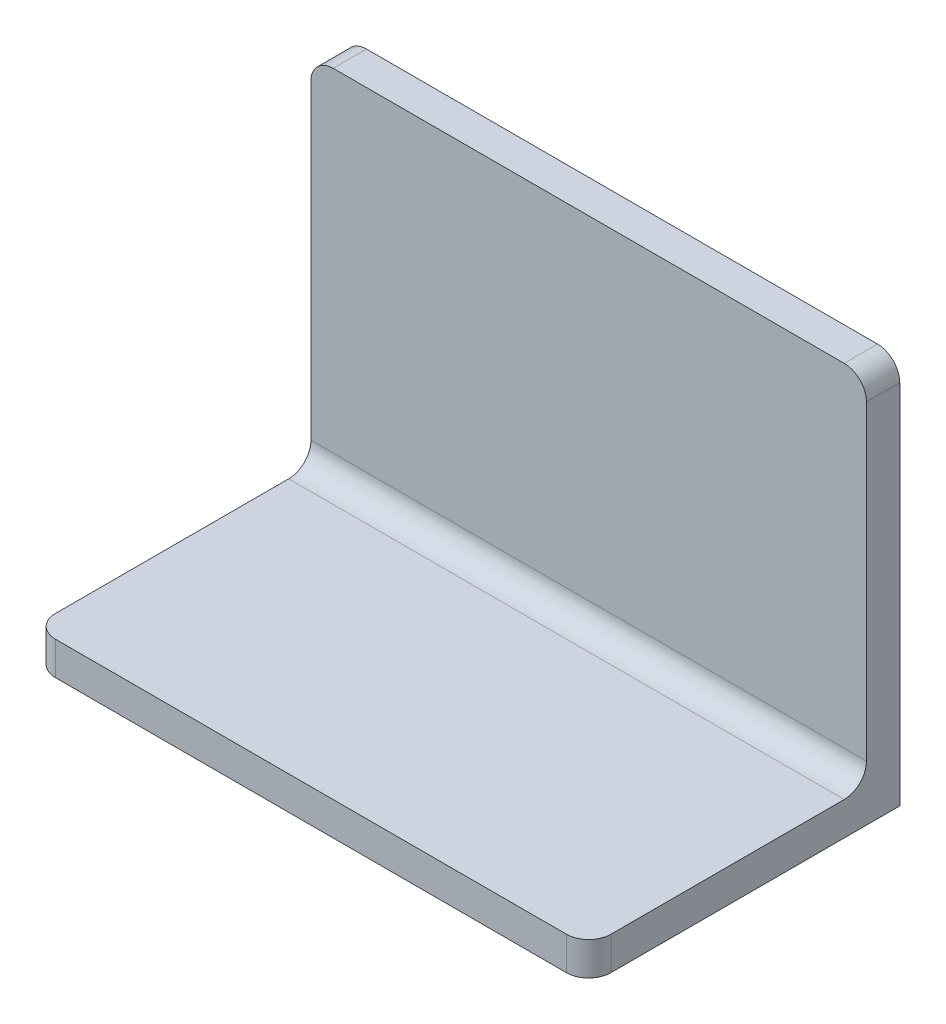
SolidWorks part; units mm, degrees
ref_plane "Front Plane" through (0, 0, 0) normal (0, 0, 1) x (1, 0, 0)
ref_plane "Top Plane" through (0, 0, 0) normal (0, 1, 0) x (1, 0, 0)
ref_plane "Right Plane" through (0, 0, 0) normal (1, 0, 0) x (0, 0, -1)
sketch "Sketch1" plane through (0, 0, 0) normal (0, 0, 1) x (1, 0, 0)
  line L1 (-25, -17.5) -> (25, -17.5)
  line L2 (-25, -17.5) -> (-25, 17.5)
  line L3 (-25, 17.5) -> (25, 17.5)
  line L4 (25, -17.5) -> (25, 17.5)
  line L5 (-25, -17.5) -> (25, 17.5) construction
  line L6 (-25, 17.5) -> (25, -17.5) construction
  point P0 (0, 0)
  dimension "D1" = 35
  dimension "D2" = 50
extrude "Boss-Extrude1" add sketch "Sketch1" along normal blind 3
sketch "Sketch3" plane through (0, 0, 3) normal (0, 0, 1) x (1, 0, 0)
  line L0 (25, -17.5) -> (25, 17.5) construction
  line L1 (-25, -17.5) -> (25, -17.5)
  line L2 (-25, -17.5) -> (-25, -14.5)
  line L3 (-25, -14.5) -> (25, -14.5)
  line L4 (25, -17.5) -> (25, -14.5)
  dimension "D1" = 3
extrude "Boss-Extrude2" add sketch "Sketch3" along normal blind 25
fillet "Fillet1" radius 2 1 edges at (0, -14.5, 3)
fillet "Fillet2" radius 2 4 edges at (-25, 17.5, 1.5) (25, 17.5, 1.5) (25, -16, 28) (-25, -16, 28)
